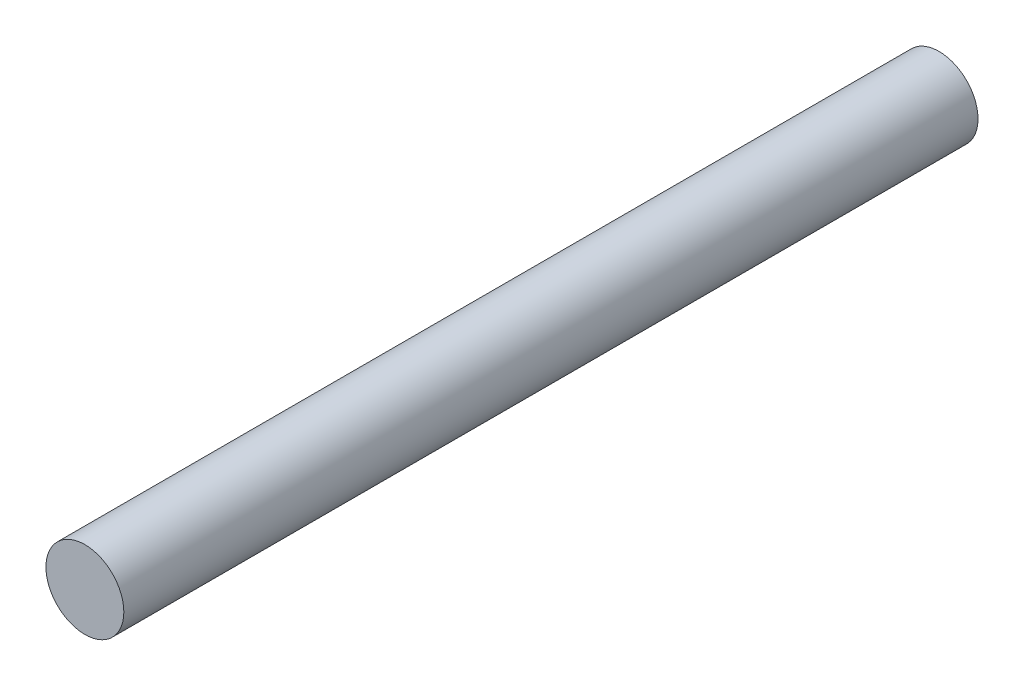
SolidWorks part; units mm, degrees
ref_plane "Front Plane" through (0, 0, 0) normal (0, 0, 1) x (1, 0, 0)
ref_plane "Top Plane" through (0, 0, 0) normal (0, 1, 0) x (1, 0, 0)
ref_plane "Right Plane" through (0, 0, 0) normal (1, 0, 0) x (0, 0, -1)
sketch "Sketch1" plane through (0, 0, 0) normal (0, 0, 1) x (1, 0, 0)
  circle A0 centre (0, 0) radius 9.12
  dimension "D1" = 18.24
extrude "Boss-Extrude1" add sketch "Sketch1" along normal blind 200
